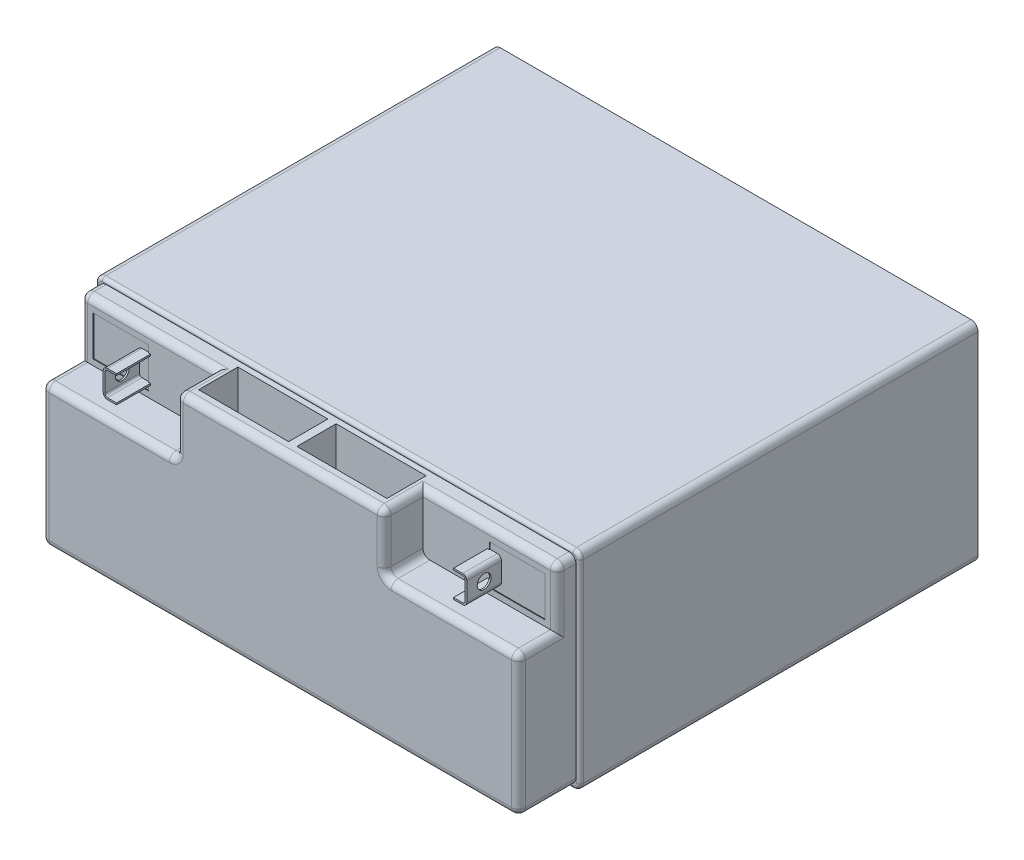
SolidWorks part; units mm, degrees
ref_plane "Front Plane" through (0, 0, 0) normal (0, 0, 1) x (1, 0, 0)
ref_plane "Top Plane" through (0, 0, 0) normal (0, 1, 0) x (1, 0, 0)
ref_plane "Right Plane" through (0, 0, 0) normal (1, 0, 0) x (0, 0, -1)
ref_plane "Plane1" through (0, -62.2132, 0) normal (0, -1, 0) x (1, 0, 0)
sketch "Sketch1" plane through (0, -62.2132, 0) normal (0, -1, 0) x (1, 0, 0)
  line L0 (-33.1131, 0) -> (144.6869, 0)
  line L1 (144.6869, 0) -> (144.6869, 146.05)
  line L2 (144.6869, 146.05) -> (-33.1131, 146.05)
  line L3 (-33.1131, 146.05) -> (-33.1131, 0)
extrude "Boss-Extrude1" add sketch "Sketch1" against normal blind 76.2
sketch "Sketch2" plane through (0, 0, 146.05) normal (0, 0, 1) x (1, 0, 0)
  line L0 (143.2096, 12.5094) -> (143.2096, -60.7358)
  line L1 (143.2096, -60.7358) -> (-31.6357, -60.7358)
  line L2 (-31.6357, -60.7358) -> (-31.6357, 12.5094)
  line L3 (-31.6357, 12.5094) -> (143.2096, 12.5094)
extrude "Boss-Extrude2" add sketch "Sketch2" along normal blind 21.082
sketch "Sketch3" plane through (0, 0, 167.132) normal (0, 0, 1) x (1, 0, 0)
  line L0 (-31.6357, 12.5094) -> (-31.6357, -8.8266)
  line L1 (-31.6357, -8.8266) -> (17.6403, -8.8266)
  line L2 (17.6403, -8.8266) -> (17.6403, 12.5094)
  line L3 (17.6403, 12.5094) -> (-31.6357, 12.5094)
extrude "Cut-Extrude1" cut sketch "Sketch3" against normal blind 14.224
sketch "Sketch4" plane through (0, 0, 152.908) normal (0, 0, 1) x (1, 0, 0)
  line L0 (-6.7872, 5.3949) -> (-6.7872, 7.9428)
  line L1 (-6.7872, 7.9428) -> (-27.0726, 7.9428)
  line L2 (-27.0726, 7.9428) -> (-27.0726, -6.6776)
  line L3 (-27.0726, -6.6776) -> (-6.7872, -6.6776)
  line L4 (-6.7872, -6.6776) -> (-6.7872, -4.5374)
  line L5 (-6.7872, -4.5374) -> (-10.918, -4.5374)
  line L6 (-10.918, -4.5374) -> (-10.918, 5.3949)
  line L7 (-10.918, 5.3949) -> (-6.7872, 5.3949)
extrude "Cut-Extrude2" cut sketch "Sketch4" against normal blind 0.254
sketch "Sketch5" plane through (0, 0, 152.908) normal (0, 0, 1) x (1, 0, 0)
  line L0 (-6.018, -4.5374) -> (-10.918, -4.5374)
  line L1 (-10.918, -4.5374) -> (-10.918, 5.3949)
  line L2 (-10.918, 5.3949) -> (-6.018, 5.3949)
  line L3 (-6.018, 5.3949) -> (-6.018, -4.5374)
extrude "Boss-Extrude3" add sketch "Sketch5" along normal blind 12.446
sketch "Sketch6" plane through (-6.018, 0, 0) normal (1, 0, 0) x (0, 0, -1)
  line L0 (-152.908, -3.9265) -> (-152.908, 4.784)
  line L1 (-152.908, 4.784) -> (-165.354, 4.784)
  line L2 (-165.354, 4.784) -> (-165.354, -3.9265)
  line L3 (-165.354, -3.9265) -> (-152.908, -3.9265)
extrude "Cut-Extrude3" cut sketch "Sketch6" against normal blind 4.289
sketch "Sketch7" plane through (0, 0, 152.908) normal (0, 0, 1) x (1, 0, 0)
  line L0 (-6.7872, 4.784) -> (-10.3071, 4.784)
  line L1 (-10.3071, 4.784) -> (-10.3071, -3.9265)
  line L2 (-10.3071, -3.9265) -> (-6.7872, -3.9265)
  line L3 (-6.7872, -3.9265) -> (-6.7872, 4.784)
extrude "Cut-Extrude4" cut sketch "Sketch7" against normal blind 0.254
sketch "Sketch8" plane through (0, 12.5094, 0) normal (0, 1, 0) x (-1, 0, 0)
  line L0 (-143.2096, 152.908) -> (-93.9336, 152.908)
  line L1 (-93.9336, 152.908) -> (-93.9336, 167.132)
  line L2 (-93.9336, 167.132) -> (-143.2096, 167.132)
  line L3 (-143.2096, 167.132) -> (-143.2096, 152.908)
extrude "Cut-Extrude5" cut sketch "Sketch8" against normal blind 21.336
sketch "Sketch9" plane through (0, 0, 152.908) normal (0, 0, 1) x (1, 0, 0)
  line L0 (118.361, 7.9428) -> (118.361, 5.3949)
  line L1 (118.361, 5.3949) -> (122.4919, 5.3949)
  line L2 (122.4919, 5.3949) -> (122.4919, -4.5374)
  line L3 (122.4919, -4.5374) -> (118.361, -4.5374)
  line L4 (118.361, -4.5374) -> (118.361, -6.6776)
  line L5 (118.361, -6.6776) -> (138.6465, -6.6776)
  line L6 (138.6465, -6.6776) -> (138.6465, 7.9428)
  line L7 (138.6465, 7.9428) -> (118.361, 7.9428)
extrude "Cut-Extrude6" cut sketch "Sketch9" against normal blind 0.254
sketch "Sketch10" plane through (0, 0, 152.908) normal (0, 0, 1) x (1, 0, 0)
  line L0 (117.5919, 5.3949) -> (122.4919, 5.3949)
  line L1 (122.4919, 5.3949) -> (122.4919, -4.5374)
  line L2 (122.4919, -4.5374) -> (117.5919, -4.5374)
  line L3 (117.5919, -4.5374) -> (117.5919, 5.3949)
extrude "Boss-Extrude4" add sketch "Sketch10" along normal blind 12.446
sketch "Sketch11" plane through (117.5919, 0, 0) normal (-1, 0, 0) x (0, 0, 1)
  line L0 (152.908, 4.784) -> (152.908, -3.9265)
  line L1 (152.908, -3.9265) -> (165.354, -3.9265)
  line L2 (165.354, -3.9265) -> (165.354, 4.784)
  line L3 (165.354, 4.784) -> (152.908, 4.784)
extrude "Cut-Extrude7" cut sketch "Sketch11" against normal blind 4.289
sketch "Sketch12" plane through (0, 0, 152.908) normal (0, 0, 1) x (1, 0, 0)
  line L0 (121.8809, -3.9265) -> (121.8809, 4.784)
  line L1 (121.8809, 4.784) -> (118.361, 4.784)
  line L2 (118.361, 4.784) -> (118.361, -3.9265)
  line L3 (118.361, -3.9265) -> (121.8809, -3.9265)
extrude "Cut-Extrude8" cut sketch "Sketch12" against normal blind 0.254
sketch "Sketch13" plane through (0, -60.7358, 0) normal (0, -1, 0) x (1, 0, 0)
  line L0 (-8.7757, 147.6421) -> (54.7243, 147.6421)
  line L1 (54.7243, 147.6421) -> (54.7243, 162.8434)
  line L2 (54.7243, 162.8434) -> (-8.7757, 162.8434)
  line L3 (-8.7757, 162.8434) -> (-8.7757, 147.6421)
extrude "Cut-Extrude9" cut sketch "Sketch13" against normal blind 19.558
sketch "Sketch14" plane through (0, -60.7358, 0) normal (0, -1, 0) x (1, 0, 0)
  line L0 (56.8496, 147.6421) -> (120.3496, 147.6421)
  line L1 (120.3496, 147.6421) -> (120.3496, 162.8434)
  line L2 (120.3496, 162.8434) -> (56.8496, 162.8434)
  line L3 (56.8496, 162.8434) -> (56.8496, 147.6421)
extrude "Cut-Extrude10" cut sketch "Sketch14" against normal blind 19.558
sketch "Sketch15" plane through (0, 12.5094, 0) normal (0, 1, 0) x (-1, 0, 0)
  line L0 (-21.2429, 162.5135) -> (-54.2629, 162.5135)
  line L1 (-54.2629, 162.5135) -> (-54.2629, 148.1138)
  line L2 (-54.2629, 148.1138) -> (-21.2429, 148.1138)
  line L3 (-21.2429, 148.1138) -> (-21.2429, 162.5135)
extrude "Cut-Extrude11" cut sketch "Sketch15" against normal blind 19.05
sketch "Sketch16" plane through (0, 12.5094, 0) normal (0, 1, 0) x (-1, 0, 0)
  line L0 (-57.3109, 162.5135) -> (-90.3309, 162.5135)
  line L1 (-90.3309, 162.5135) -> (-90.3309, 148.1138)
  line L2 (-90.3309, 148.1138) -> (-57.3109, 148.1138)
  line L3 (-57.3109, 148.1138) -> (-57.3109, 162.5135)
extrude "Cut-Extrude12" cut sketch "Sketch16" against normal blind 19.05
hole_wizard "Hole1" positions "Sketch18" profile "Sketch17" legacy
sketch "Sketch18" plane through (122.4919, 0, 0) normal (1, 0, 0) x (0, 0, -1)
  point P0 (-159.004, 0.4288)
sketch "Sketch17" plane through (122.4919, 0.4288, 159.004) normal (0, 1, 0) x (0, 0, -1)
  line L0 (0, 0) -> (0, 0.6109)
  line L1 (0, 0.6109) -> (2.54, 0.6109)
  line L2 (2.54, 0.6109) -> (2.54, 0)
  line L3 (2.54, 0) -> (0, 0)
  line L4 (0, 110) -> (0, -10) construction
  dimension "Diameter" = 5.08
  dimension "Depth" = 0.6109
hole_wizard "Hole2" positions "Sketch20" profile "Sketch19" legacy
sketch "Sketch20" plane through (-10.918, 0, 0) normal (-1, 0, 0) x (0, 0, 1)
  point P0 (159.004, 0.4288)
sketch "Sketch19" plane through (-10.918, 0.4288, 159.004) normal (0, 1, 0) x (0, 0, 1)
  line L0 (0, 0) -> (0, 0.6109)
  line L1 (0, 0.6109) -> (2.54, 0.6109)
  line L2 (2.54, 0.6109) -> (2.54, 0)
  line L3 (2.54, 0) -> (0, 0)
  line L4 (0, 110) -> (0, -10) construction
  dimension "Diameter" = 5.08
  dimension "Depth" = 0.6109
fillet "Fillet1" radius 2.54 26 edges at (-31.6357, -60.7358, 156.591) (-31.6357, 12.5094, 149.479) (-31.6357, 1.8414, 152.908) (143.2096, -60.7358, 156.591) (55.7869, -60.7358, 167.132) (-31.6357, -34.7812, 167.132) (-31.6357, -8.8266, 160.02) (-6.9977, 12.5094, 152.908) (143.2096, 12.5094, 149.479) (143.2096, 1.8414, 152.908) (143.2096, -34.7812, 167.132) (143.2096, -8.8266, 160.02) (-6.9977, -8.8266, 167.132) (17.6403, 1.8414, 167.132) (17.6403, 12.5094, 160.02) (118.5716, 12.5094, 152.908) (93.9336, 1.8414, 167.132) (118.5716, -8.8266, 167.132) (55.7869, 12.5094, 167.132) (93.9336, 12.5094, 160.02) (17.6403, -8.8266, 160.02) (144.6869, 13.9868, 73.025) (93.9336, -8.8266, 160.02) (-33.1131, -62.2132, 73.025) (144.6869, -62.2132, 73.025) (-33.1131, 13.9868, 73.025)
fillet "Fillet2" radius 0.9131 4 edges at (121.8809, -3.9265, 159.004) (-10.3071, -3.9265, 159.004) (121.8809, 4.784, 159.004) (-10.3071, 4.784, 159.004)
fillet "Fillet3" radius 1.27 8 edges at (-33.1131, -24.1132, 146.05) (-32.3691, 13.2428, 146.05) (-32.3691, -61.4693, 146.05) (55.7869, 13.9868, 146.05) (55.7869, -62.2132, 146.05) (143.943, 13.2428, 146.05) (143.943, -61.4693, 146.05) (144.6869, -24.1132, 146.05)
fillet "Fillet4" radius 1.524 4 edges at (122.4919, -4.5374, 159.004) (-10.918, 5.3949, 159.004) (-10.918, -4.5374, 159.004) (122.4919, 5.3949, 159.004)
